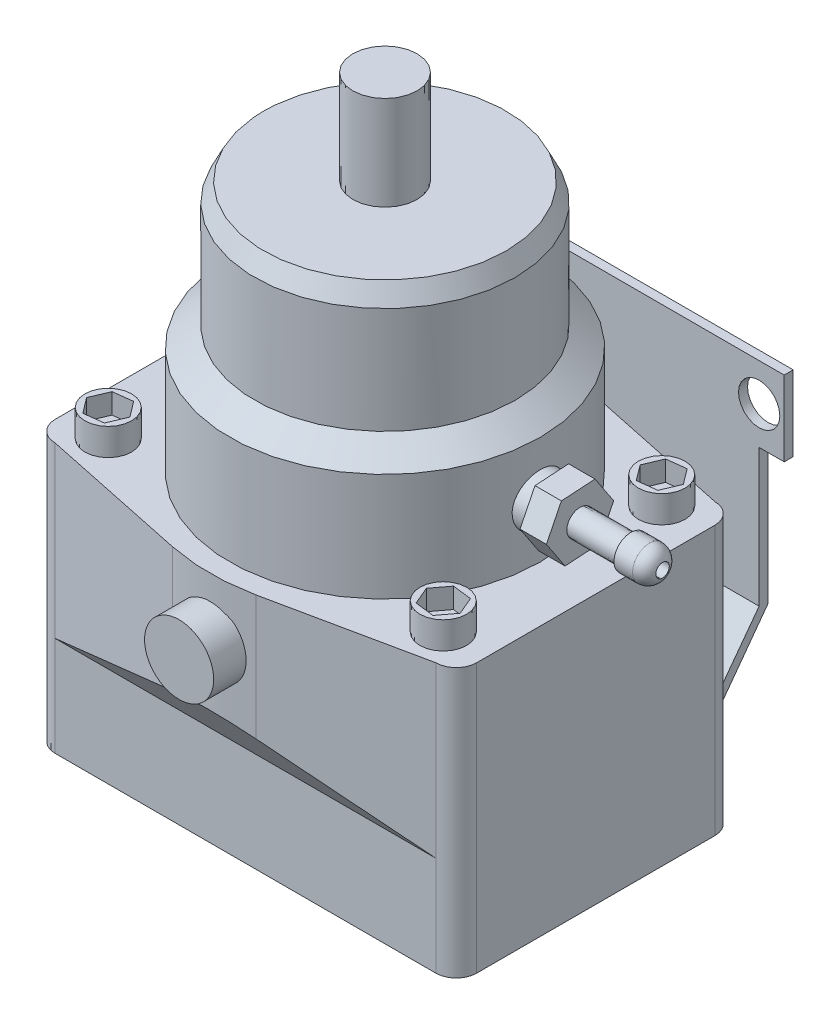
SolidWorks part; units mm, degrees
ref_plane "Front Plane" through (0, 0, 0) normal (0, 0, 1) x (1, 0, 0)
ref_plane "Top Plane" through (0, 0, 0) normal (0, 1, 0) x (1, 0, 0)
ref_plane "Right Plane" through (0, 0, 0) normal (1, 0, 0) x (0, 0, -1)
sketch "Sketch1" plane through (0, 0, 0) normal (0, 1, 0) x (1, 0, 0)
  line L2 (28.125, -20.6) -> (-28.125, -20.6)
  line L3 (-31.125, -17.6) -> (-31.125, 17.6)
  line L4 (-28.125, 20.6) -> (28.125, 20.6)
  line L5 (31.125, -17.6) -> (31.125, 17.6)
  arc A0 (31.125, -17.6) -> (28.125, -20.6) centre (28.125, -17.6) cw
  arc A1 (31.125, 17.6) -> (28.125, 20.6) centre (28.125, 17.6) ccw
  arc A2 (-31.125, 17.6) -> (-28.125, 20.6) centre (-28.125, 17.6) cw
  arc A3 (-28.125, -20.6) -> (-31.125, -17.6) centre (-28.125, -17.6) cw
  dimension "D1" = 3
extrude "Boss-Extrude1" add sketch "Sketch1" along normal blind 39.7
ref_plane "Plane2" through (0, 39.7, 0) normal (0, 1, 0) x (1, 0, 0)
sketch "Sketch2" plane through (0, 39.7, 0) normal (0, 1, 0) x (1, 0, 0)
  line L3 (-28.125, -20.6) -> (-6.1593, -25.2079)
  line L5 (28.125, -20.6) -> (6.1593, -25.2079)
  line L7 (31.125, -17.6) -> (31.125, 17.6)
  line L8 (28.125, 20.6) -> (-28.125, 20.6)
  line L9 (-31.125, 17.6) -> (-31.125, -17.6)
  line L10 (-28.125, -20.6) -> (28.125, -20.6)
  line L14 (-28.125, -20.6) -> (28.125, -20.6)
  arc A3 (6.1593, -25.2079) -> (-6.1593, -25.2079) centre (0, 4.153) cw
  arc A7 (28.125, -20.6) -> (31.125, -17.6) centre (28.125, -17.6) ccw
  arc A8 (31.125, 17.6) -> (28.125, 20.6) centre (28.125, 17.6) ccw
  arc A9 (-28.125, 20.6) -> (-31.125, 17.6) centre (-28.125, 17.6) ccw
  arc A10 (-31.125, -17.6) -> (-28.125, -20.6) centre (-28.125, -17.6) ccw
  dimension "D2" = 30
  dimension "D1" = 0
extrude "Boss-Extrude2" add sketch "Sketch2" against normal blind 25
ref_plane "Plane4" through (31.125, 0, 0) normal (1, 0, 0) x (0, 0, -1)
sketch "Sketch3" plane through (31.125, 0, 0) normal (1, 0, 0) x (0, 0, -1)
  line L0 (-20.6, 14.7) -> (-20.6, 22.2)
  line L1 (-20.6, 39.7) -> (-20.6, 14.7) construction
  line L2 (-20.6, 14.7) -> (-25.847, 22.2)
  line L3 (-25.847, 39.7) -> (-25.847, 14.7) construction
  line L4 (-25.847, 22.2) -> (-31.5526, 18.2083)
  line L5 (-31.5526, 18.2083) -> (-32.7446, 11.4644)
  line L6 (-32.7446, 11.4644) -> (-24.8173, 11.4644)
  line L7 (-24.8173, 11.4644) -> (-20.6, 14.7)
extrude "Cut-Extrude1" cut sketch "Sketch3" against normal blind 100 contours L6 L7 L2 L4 L5
ref_plane "Plane5" through (0, 0, -20.6) normal (0, 0, -1) x (-1, 0, 0)
ref_plane "Plane6" through (-31.125, 0, 0) normal (-1, 0, 0) x (0, 0, 1)
sketch "Sketch5" plane through (-31.125, 0, 0) normal (-1, 0, 0) x (0, 0, 1)
  circle A0 centre (0, 17.1) radius 9.905
extrude "Cut-Extrude3" cut sketch "Sketch5" against normal blind 21.5
ref_plane "Plane7" through (31.125, 0, 0) normal (1, 0, 0) x (0, 0, -1)
ref_plane "Plane8" through (0, 0, 0) normal (0, -1, 0) x (-1, 0, 0)
sketch "Sketch6" plane through (0, 0, 0) normal (0, -1, 0) x (-1, 0, 0)
  line L0 (0, -20.6) -> (0, 20.6)
  line L1 (-28.125, -20.6) -> (28.125, -20.6) construction
  line L2 (21.835, 20.6) -> (-21.835, 20.6) construction
  line L3 (0, 0) -> (-31.125, 0)
  line L4 (-31.125, 19.36) -> (-31.125, -19.36) construction
  line L5 (0, 0) -> (31.125, 0)
  line L6 (31.125, -19.36) -> (31.125, 19.36) construction
  circle A0 centre (0, 0) radius 6.25
extrude "Cut-Extrude4" cut sketch "Sketch6" against normal blind 37 contours A0
mirror "Mirror1" about plane through (0, 0, 0) normal (0, 0, 1) of "Cut-Extrude1", "Boss-Extrude2"
sketch "Sketch8" plane through (0, 0, 0) normal (0, 0, 1) x (1, 0, 0)
  line L0 (0, 76.95) -> (0, 39.7)
  line L1 (28.4317, 39.7) -> (-28.4317, 39.7) construction
  line L5 (0, 39.7) -> (22.95, 39.7)
  line L6 (22.95, 39.7) -> (22.95, 55.6434)
  line L7 (17.9047, 76.95) -> (0, 76.95)
  line L9 (19.2429, 58.5214) -> (19.2429, 74.2214)
  line L12 (22.95, 55.6434) -> (19.2429, 58.5214)
  line L13 (19.2429, 74.2214) -> (17.9047, 76.95)
  point P1 (0, 0)
revolve "Revolve1" add sketch "Sketch8" angle 360 about L0
sketch "Sketch10" plane through (31.125, 0, 0) normal (1, 0, 0) x (0, 0, -1)
  line L0 (20.6, 0) -> (22.1, 0)
  line L1 (22.1, 0) -> (22.1, 12.5)
  line L2 (22.1, 12.5) -> (29.1569, 22.0817)
  line L3 (29.1569, 22.0817) -> (29.1569, 53.7817)
  line L4 (20.6, 0) -> (20.6, 12.6807)
  line L5 (20.6, 14.7) -> (20.6, 0) construction
  line L6 (20.6, 12.6807) -> (27.8213, 22.3743)
  line L7 (27.8213, 22.3743) -> (27.8213, 53.7817)
  line L8 (27.8213, 53.7817) -> (29.1569, 53.7817)
extrude "Boss-Extrude4" add sketch "Sketch10" against normal up to surface (62.25 mm away) up to face at (-31.125, 17.1, 9.905)
ref_plane "Plane10" through (0, 0, -32.1569) normal (0, 0, -1) x (-1, 0, 0)
sketch "Sketch11" plane through (0, 0, -32.1569) normal (0, 0, -1) x (-1, 0, 0)
  line L0 (31.125, 53.7817) -> (31.125, 42.6817)
  line L1 (31.125, 53.7817) -> (31.125, 22.0817) construction
  line L2 (31.125, 42.6817) -> (27.425, 42.6817)
  line L3 (27.425, 42.6817) -> (27.425, 22.0817)
  line L4 (31.125, 22.0817) -> (-31.125, 22.0817) construction
  line L5 (0, 22.0817) -> (0, 53.7817)
  line L6 (31.125, 53.7817) -> (-31.125, 53.7817) construction
  line L7 (-27.425, 42.6817) -> (-27.425, 22.0817)
  line L8 (-31.125, 53.7817) -> (-31.125, 42.6817)
  line L9 (-31.125, 42.6817) -> (-27.425, 42.6817)
  line L10 (-27.425, 22.0817) -> (-35.7083, 22.0817)
  line L11 (-35.7083, 22.0817) -> (-35.7083, 51.9468)
  line L12 (-35.7083, 51.9468) -> (-31.125, 53.7817)
  line L13 (31.125, 53.7817) -> (39.8201, 56.4915)
  line L14 (39.8201, 56.4915) -> (37.8724, 26.8428)
  line L15 (37.8724, 26.8428) -> (31.125, 22.0817)
  line L16 (31.125, 22.0817) -> (27.425, 22.0817)
extrude "Cut-Extrude5" cut sketch "Sketch11" against normal blind 6 contours L12 L11 L10 L7 L9 L8 | L16 L15 L14 L13 L0 L2 L3
ref_plane "Plane11" through (0, -6.1567, -8.3594) normal (0, -0.593, -0.8052) x (-1, 0, 0)
sketch "Sketch12" plane through (0, -6.1567, -8.3594) normal (0, -0.593, -0.8052) x (-1, 0, 0)
  line L0 (27.425, 35.0706) -> (27.425, 23.1706)
  line L1 (31.125, 23.1706) -> (-31.125, 23.1706) construction
  line L2 (-27.425, 35.0706) -> (-27.425, 23.1706)
  line L3 (-27.425, 35.0706) -> (-41.4078, 35.0706)
  line L4 (-41.4078, 35.0706) -> (-42.2647, 23.1706)
  line L5 (-42.2647, 23.1706) -> (-27.425, 23.1706)
  line L6 (27.425, 35.0706) -> (37.56, 35.0706)
  line L7 (37.56, 35.0706) -> (37.56, 23.1706)
  line L8 (37.56, 23.1706) -> (27.425, 23.1706)
extrude "Cut-Extrude7" cut sketch "Sketch12" against normal blind 1.5
ref_plane "Plane12" through (0, 0, -22.1) normal (0, 0, -1) x (-1, 0, 0)
sketch "Sketch13" plane through (0, 0, -22.1) normal (0, 0, -1) x (-1, 0, 0)
  line L0 (-27.425, 13.2774) -> (-27.425, 0)
  line L1 (31.125, 0) -> (-31.125, 0) construction
  line L2 (-27.425, 0) -> (-32.7843, 0)
  line L3 (-32.7843, 0) -> (-32.7843, 13.2774)
  line L4 (-32.7843, 13.2774) -> (-27.425, 13.2774)
  line L5 (0, 12.5) -> (0, 0)
  line L6 (27.425, 12.5) -> (-27.425, 12.5) construction
  line L7 (27.425, 0) -> (32.7843, 0)
  line L8 (32.7843, 0) -> (32.7843, 13.2774)
  line L9 (32.7843, 13.2774) -> (27.425, 13.2774)
  line L10 (27.425, 13.2774) -> (27.425, 0)
extrude "Cut-Extrude8" cut sketch "Sketch13" against normal blind 1.5 contours L4 L3 L2 L0 | L9 L10 L7 L8
sketch "Sketch15" plane through (0, 0, -32.1569) normal (0, 0, -1) x (-1, 0, 0)
  line L0 (0, 53.7817) -> (0, 39.9358)
  line L3 (31.125, 53.7817) -> (-31.125, 53.7817) construction
  circle A0 centre (27.425, 48.2317) radius 3.05
  circle A1 centre (-27.425, 48.2317) radius 3.05
extrude "Cut-Extrude9" cut sketch "Sketch15" against normal blind 5.9 contours A0 | A1
ref_plane "Plane13" through (0, 76.95, 0) normal (0, 1, 0) x (1, 0, 0)
sketch "Sketch16" plane through (0, 76.95, 0) normal (0, 1, 0) x (1, 0, 0)
  circle A1 centre (0, 0) radius 4.75
extrude "Boss-Extrude6" add sketch "Sketch16" along normal blind 13.9
ref_plane "Plane14" through (0, 90.85, 0) normal (0, 1, 0) x (1, 0, 0)
sketch "Sketch17" plane through (0, 90.85, 0) normal (0, 1, 0) x (1, 0, 0)
  circle A1 centre (0, 0) radius 4.75 construction
  circle A3 centre (0, 0) radius 4.75
ref_plane "Plane15" through (0, 0, 25.6) normal (0, 0, 1) x (1, 0, 0)
sketch "Sketch19" plane through (0, 0, 25.6) normal (0, 0, 1) x (1, 0, 0)
  circle A0 centre (0, 30.95) radius 5.1
extrude "Boss-Extrude7" add sketch "Sketch19" along normal blind 4.8 separate body
ref_plane "Plane16" through (0, 39.7, 0) normal (0, 1, 0) x (1, 0, 0)
sketch "Sketch20" plane through (0, 39.7, 0) normal (0, 1, 0) x (1, 0, 0)
  circle A2 centre (-24.7354, 16.1281) radius 3.45
extrude "Boss-Extrude8" add sketch "Sketch20" along normal blind 4
ref_plane "Plane17" through (0, 143.7, 0) normal (0, 1, 0) x (1, 0, 0)
sketch "Sketch21" plane through (0, 143.7, 0) normal (0, 1, 0) x (1, 0, 0)
  line L1 (-23.6172, 13.4902) -> (-21.8918, 15.7775)
  line L2 (-21.8918, 15.7775) -> (-23.01, 18.4154)
  line L3 (-23.01, 18.4154) -> (-25.8536, 18.766)
  line L4 (-25.8536, 18.766) -> (-27.579, 16.4786)
  line L5 (-27.579, 16.4786) -> (-26.4608, 13.8407)
  line L6 (-26.4608, 13.8407) -> (-23.6172, 13.4902)
extrude "Cut-Extrude10" cut sketch "Sketch21" against normal blind 103
mirror "Mirror2" about plane through (0, 0, 0) normal (1, 0, 0) of "Boss-Extrude8", "Cut-Extrude10"
mirror "Mirror3" about plane through (0, 0, 0) normal (0, 0, 1) of "Mirror2", "Boss-Extrude8", "Cut-Extrude10"
sketch "Sketch22" plane through (0, 0, -22.1) normal (0, 0, -1) x (-1, 0, 0)
  line L0 (0, 12.5) -> (0, 0)
  line L1 (27.425, 12.5) -> (-27.425, 12.5) construction
  line L5 (-16.3579, 3.761) -> (-14.9148, 6.3573)
  line L6 (-14.9148, 6.3573) -> (-16.4416, 8.9052)
  line L7 (-16.4416, 8.9052) -> (-19.4117, 8.8569)
  line L8 (-19.4117, 8.8569) -> (-20.8548, 6.2606)
  line L9 (-20.8548, 6.2606) -> (-19.3279, 3.7126)
  line L10 (-19.3279, 3.7126) -> (-16.3579, 3.761)
  circle A0 centre (-17.8848, 6.3089) radius 3.9
  circle A1 centre (-17.8848, 6.3089) radius 2.5725 construction
extrude "Boss-Extrude9" add sketch "Sketch22" along normal blind 5.6 contours A0
ref_plane "Plane18" through (0, 0, -27.7) normal (0, 0, -1) x (-1, 0, 0)
sketch "Sketch23" plane through (0, 0, -27.7) normal (0, 0, -1) x (-1, 0, 0)
  line L1 (-16.3524, 3.8414) -> (-14.9816, 6.4022)
  line L2 (-14.9816, 6.4022) -> (-16.514, 8.8698)
  line L3 (-16.514, 8.8698) -> (-19.4172, 8.7765)
  line L4 (-19.4172, 8.7765) -> (-20.7879, 6.2156)
  line L5 (-20.7879, 6.2156) -> (-19.2556, 3.7481)
  line L6 (-19.2556, 3.7481) -> (-16.3524, 3.8414)
  circle A0 centre (-17.8848, 6.3089) radius 2.5155 construction
extrude "Cut-Extrude11" cut sketch "Sketch23" against normal blind 3.6
mirror "Mirror4" about plane through (0, 0, 0) normal (1, 0, 0) of "Boss-Extrude9", "Cut-Extrude11"
ref_plane "Plane19" through (22, 0, 0) normal (1, 0, 0) x (0, 0, -1)
sketch "Sketch24" plane through (22, 0, 0) normal (1, 0, 0) x (0, 0, -1)
  circle A0 centre (0, 47.6717) radius 3.85
extrude "Boss-Extrude10" add sketch "Sketch24" along normal blind 2.9
ref_plane "Plane20" through (24.9, 0, 0) normal (1, 0, 0) x (0, 0, -1)
sketch "Sketch25" plane through (24.9, 0, 0) normal (1, 0, 0) x (0, 0, -1)
  line L1 (2.7512, 43.5279) -> (4.9643, 47.9824)
  line L2 (4.9643, 47.9824) -> (2.2131, 52.1262)
  line L3 (2.2131, 52.1262) -> (-2.7512, 51.8156)
  line L4 (-2.7512, 51.8156) -> (-4.9643, 47.3611)
  line L5 (-4.9643, 47.3611) -> (-2.2131, 43.2172)
  line L6 (-2.2131, 43.2172) -> (2.7512, 43.5279)
  circle A0 centre (0, 47.6717) radius 4.3076 construction
extrude "Boss-Extrude11" add sketch "Sketch25" along normal blind 3.9
ref_plane "Plane21" through (28.8, 0, 0) normal (1, 0, 0) x (0, 0, -1)
sketch "Sketch27" plane through (28.8, 0, 0) normal (1, 0, 0) x (0, 0, -1)
  circle A0 centre (0, 47.6717) radius 1.95
extrude "Boss-Extrude12" add sketch "Sketch27" along normal blind 7.5
ref_plane "Plane22" through (36.3, 0, 0) normal (1, 0, 0) x (0, 0, -1)
sketch "Sketch28" plane through (36.3, 0, 0) normal (1, 0, 0) x (0, 0, -1)
  circle A2 centre (0, 47.6717) radius 2.5
extrude "Boss-Extrude13" add sketch "Sketch28" along normal blind 4.75
fillet "Fillet3" radius 2 1 edges at (41.05, 47.6717, -2.5)
ref_plane "Plane23" through (41.05, 0, 0) normal (1, 0, 0) x (0, 0, -1)
sketch "Sketch29" plane through (41.05, 0, 0) normal (1, 0, 0) x (0, 0, -1)
  circle A1 centre (0, 47.6717) radius 1
extrude "Cut-Extrude12" cut sketch "Sketch29" against normal blind 23.75
sketch "Sketch30" plane through (0, 90.85, 0) normal (0, 1, 0) x (1, 0, 0)
  circle A1 centre (0, 0) radius 4.75
  circle A2 centre (0, 0) radius 4.75
  dimension "D1" = 0
curve "Helix/Spiral2" pitch 1 height 13 turns 13
ref_plane "Plane24" through (0, 0, 3.3588) normal (0, 0, 1) x (1, 0, 0)
sketch "Sketch31" plane through (0, 0, 3.3588) normal (0, 0, 1) x (1, 0, 0)
  circle A0 centre (-3.2781, 90.8223) radius 0.016
sweep "Cut-Sweep3" cut profiles "Sketch31" path "Helix/Spiral2"
